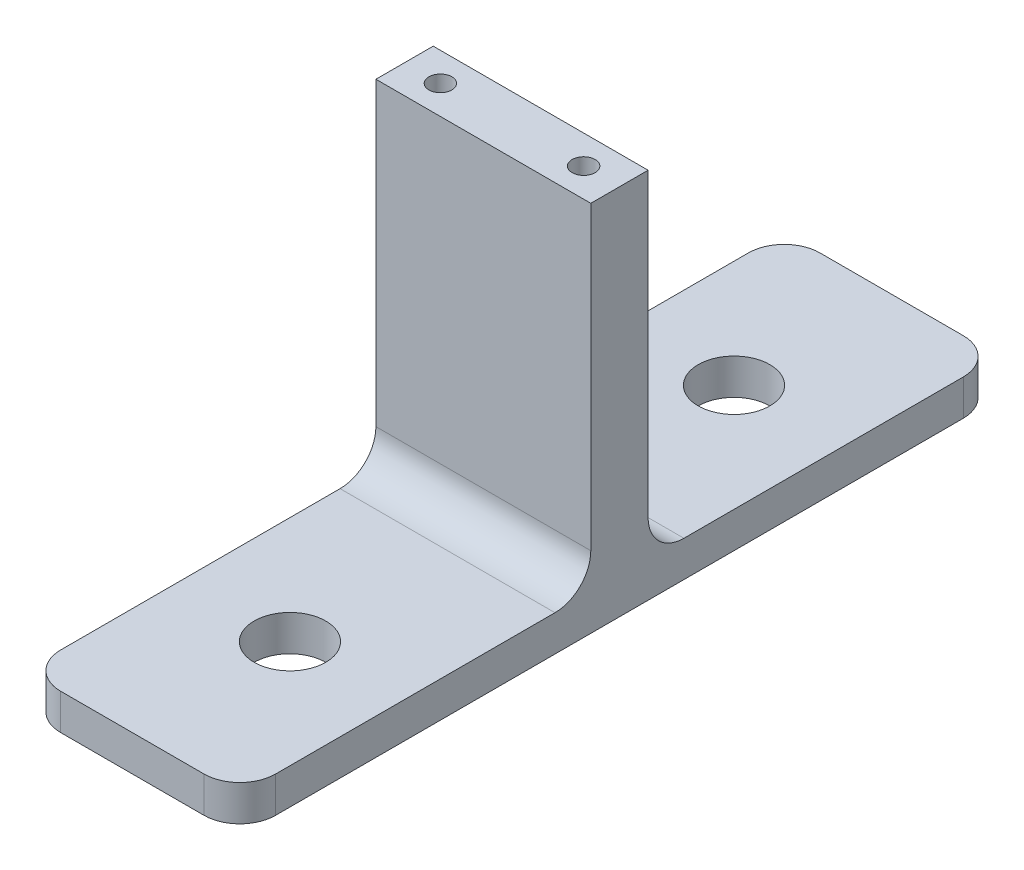
SolidWorks part; units mm, degrees
ref_plane "Front Plane" through (0, 0, 0) normal (0, 0, 1) x (1, 0, 0)
ref_plane "Top Plane" through (0, 0, 0) normal (0, 1, 0) x (1, 0, 0)
ref_plane "Right Plane" through (0, 0, 0) normal (1, 0, 0) x (0, 0, -1)
sketch "Sketch1" plane through (0, 0, 0) normal (1, 0, 0) x (0, 0, -1)
  line L1 (0, 0) -> (57, 0)
  line L2 (0, 0) -> (0, 5)
  line L3 (0, 5) -> (57, 5)
  line L4 (57, 0) -> (57, 5)
  dimension "D1" = 5
  dimension "D2" = 57
extrude "Boss-Extrude1" add sketch "Sketch1" along normal blind 30 contours L3 L4 L1 L2
sketch "Sketch2" plane through (0, 5, 0) normal (0, 1, 0) x (1, 0, 0)
  line L0 (30, 0) -> (30, 57) construction
  line L1 (0, 57) -> (30, 57)
  line L2 (0, 57) -> (0, 49)
  line L3 (0, 49) -> (30, 49)
  line L4 (30, 57) -> (30, 49)
  dimension "D1" = 8
extrude "Boss-Extrude2" add sketch "Sketch2" along normal blind 47
sketch "Sketch3" plane through (0, 5, 0) normal (0, 1, 0) x (1, 0, 0)
  line L0 (30, 0) -> (0, 0) construction
  circle A0 centre (15, 22) radius 5
  point P4 (15, 0)
  dimension "D2" = 10
  dimension "D1" = 22
extrude "Cut-Extrude1" cut sketch "Sketch3" against normal through all
sketch "Sketch5" plane through (0, 52, 0) normal (0, 1, 0) x (1, 0, 0)
  line L0 (0, 57) -> (0, 49) construction
  line L1 (30, 49) -> (30, 57) construction
  circle A0 centre (5, 53) radius 1.6
  circle A1 centre (25, 53) radius 1.6
  point P5 (0, 53)
  dimension "D1" = 3.2
  dimension "D3" = 5
  dimension "D2" = 5
extrude "Cut-Extrude3" cut sketch "Sketch5" against normal blind 14
fillet "Fillet1" radius 5 4 edges at (15, 0, -57) (15, 5, -49) (0, 2.5, 0) (30, 2.5, 0)
ref_plane "Plane1" through (0, 0, -53) normal (0, 0, -1) x (-1, 0, 0)
mirror "Mirror1" about plane through (0, 0, -53) normal (0, 0, -1) of "Boss-Extrude1", "Cut-Extrude1"
fillet "Fillet2" radius 5 3 edges at (15, 5, -57) (0, 2.5, -106) (30, 2.5, -106)
